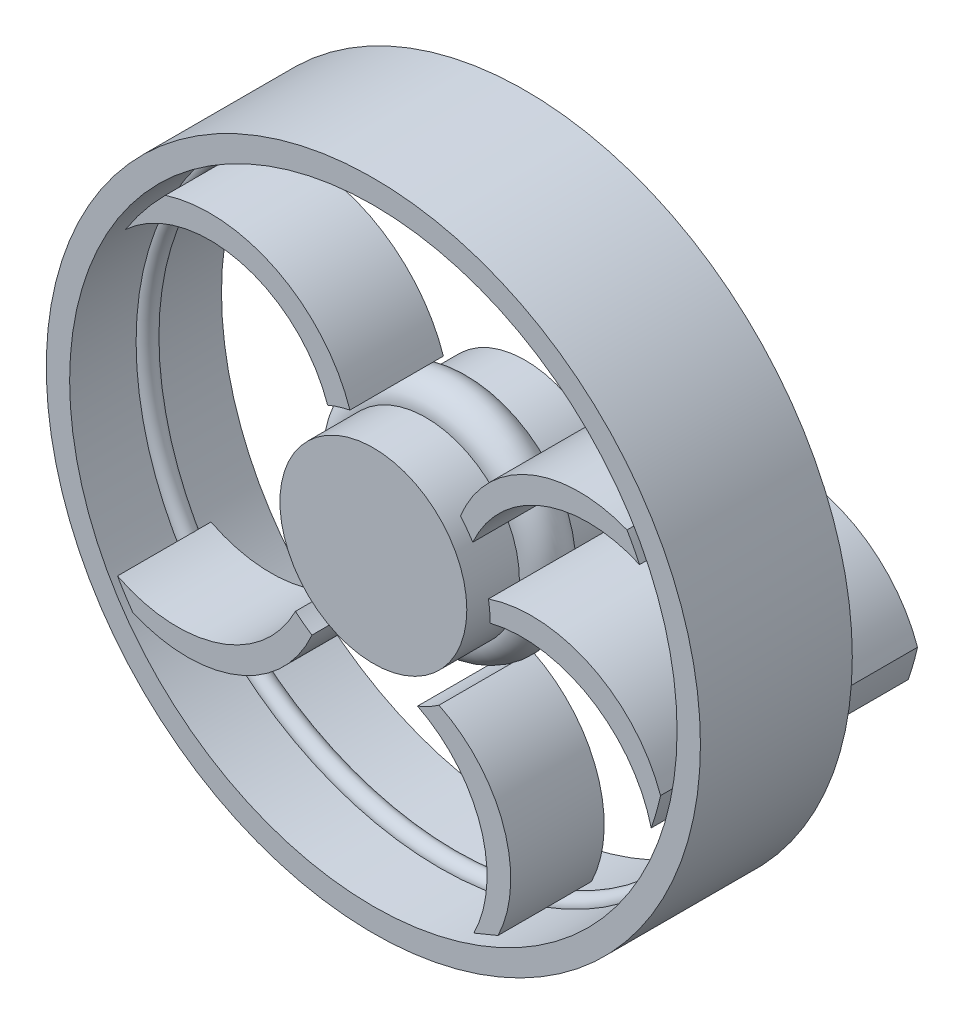
SolidWorks part; units mm, degrees
ref_plane "Front Plane" through (0, 0, 0) normal (0, 0, 1) x (1, 0, 0)
ref_plane "Top Plane" through (0, 0, 0) normal (0, 1, 0) x (1, 0, 0)
ref_plane "Right Plane" through (0, 0, 0) normal (1, 0, 0) x (0, 0, -1)
sketch "Sketch1" plane through (0, 0, 0) normal (0, 1, 0) x (1, 0, 0)
  line L0 (0, 0) -> (0, 65)
  line L1 (40, 65) -> (40, 42.5)
  line L2 (0, 65) -> (40, 65)
  line L3 (40, 22.5) -> (40, 0)
  line L4 (0, 0) -> (40, 0)
  line L5 (130, 36.5517) -> (130, 65)
  line L6 (140, 65) -> (140, 0)
  line L8 (140, 0) -> (130, 0)
  line L9 (130, 0) -> (130, 28.4483)
  line L10 (130, 65) -> (140, 65)
  arc A0 (40, 22.5) -> (40, 42.5) centre (40, 32.5) ccw
  arc A1 (130, 36.5517) -> (130, 28.4483) centre (130, 32.5) ccw
  dimension "D4" = 10
  dimension "D1" = 65
  dimension "D2" = 40
  dimension "D3" = 100
  dimension "D5" = 10
revolve "Revolve3" add sketch "Sketch1" angle 360 about L0
sketch "Sketch2" plane through (0, 0, 0) normal (0, 0, 1) x (1, 0, 0)
  arc A0 (-89.0385, 89.0792) -> (-10.0164, 48.9865) centre (-69.9577, 28.7652) cw
  circle A1 centre (0, 0) radius 125.9483 construction
  circle A2 centre (0, 0) radius 50 construction
  arc A3 (-106.0693, 67.9137) -> (-19.5672, 46.0122) centre (-69.9577, 28.7652) cw
  arc A4 (-86.0223, 79.5449) -> (-19.4917, 45.7899) centre (-69.9577, 28.7652) cw construction
  arc A5 (-89.0792, -89.0385) -> (-67.9137, -106.0693) centre (0, 0) ccw
  arc A6 (67.9137, 106.0693) -> (46.0122, 19.5672) centre (28.7652, 69.9577) cw
  arc A7 (89.0792, 89.0385) -> (48.9865, 10.0164) centre (28.7652, 69.9577) cw
  arc A8 (106.0693, -67.9137) -> (19.5672, -46.0122) centre (69.9577, -28.7652) cw
  arc A9 (89.0385, -89.0792) -> (10.0164, -48.9865) centre (69.9577, -28.7652) cw
  arc A10 (-67.9137, -106.0693) -> (-46.0122, -19.5672) centre (-28.7652, -69.9577) cw
  arc A11 (-89.0792, -89.0385) -> (-48.9865, -10.0164) centre (-28.7652, -69.9577) cw
  arc A12 (89.0385, -89.0792) -> (106.0693, -67.9137) centre (0, 0) ccw
  arc A13 (89.0792, 89.0385) -> (67.9137, 106.0693) centre (0, 0) ccw
  arc A14 (-89.0385, 89.0792) -> (-106.0693, 67.9137) centre (0, 0) ccw
  arc A15 (-48.9865, -10.0164) -> (-46.0122, -19.5672) centre (0, 0) ccw
  arc A16 (-10.0164, 48.9865) -> (-19.5672, 46.0122) centre (0, 0) ccw
  arc A17 (48.9865, 10.0164) -> (46.0122, 19.5672) centre (0, 0) ccw
  arc A18 (10.0164, -48.9865) -> (19.5672, -46.0122) centre (0, 0) ccw
  circle A19 centre (0, 0) radius 40 construction
  point P36 (0, 0)
  dimension "D3" = 63.2603
  dimension "D4" = 10.0164
  dimension "D5" = 19.5672
  dimension "D1" = 10
  dimension "D2" = 4
extrude "Boss-Extrude2" add sketch "Sketch2" against normal blind 40 separate body contours A3 A16 A0 A14
sketch "Sketch5" plane through (0, 0, 0) normal (0, 0, 1) x (1, 0, 0)
  arc A0 (50, 0) -> (118.932, -41.4505) centre (63.7407, -55.1912) cw
  circle A1 centre (0, 0) radius 50 construction
  circle A2 centre (0, 0) radius 125.9483 construction
  arc A3 (49.2509, 8.6226) -> (122.9195, -27.4549) centre (67.7415, -46.8732) cw
  circle A4 centre (0, 0) radius 40 construction
  arc A5 (118.932, -41.4505) -> (122.9195, -27.4549) centre (0, 0) ccw
  arc A6 (50, 0) -> (49.2509, 8.6226) centre (0, 0) ccw
  dimension "D1" = 56.876
  dimension "D2" = 58.4952
  dimension "D3" = 49.2509
  dimension "D4" = 50
  dimension "D5" = 63.7407
  dimension "D6" = 67.7415
extrude "Boss-Extrude3" add sketch "Sketch5" against normal blind 110 separate body contours A0 A5 A3 A6
sketch "Sketch6" plane through (0, 0, 0) normal (0, 0, 1) x (1, 0, 0)
  arc A0 (-33.3349, -37.2664) -> (-109.4975, -62.2355) centre (-83.9007, -11.6696) cw
  circle A1 centre (0, 0) radius 50 construction
  circle A2 centre (0, 0) radius 125.9483 construction
  arc A3 (-26.2706, -42.5424) -> (-103.0222, -72.4527) centre (-79.6016, -19.1218) cw
  arc A4 (-109.4975, -62.2355) -> (-103.0222, -72.4527) centre (0, 0) ccw
  arc A5 (-33.3349, -37.2664) -> (-26.2706, -42.5424) centre (0, 0) ccw
  circle A6 centre (0, 0) radius 40 construction
  dimension "D1" = 56.6754
  dimension "D2" = 58.247
  dimension "D3" = 26.2706
  dimension "D4" = 33.3349
  dimension "D5" = 79.6016
  dimension "D6" = 83.9007
extrude "Boss-Extrude4" add sketch "Sketch6" against normal blind 40 separate body contours A3 A4 A0 A5
sketch "Sketch7" plane through (0, 0, 0) normal (0, 0, 1) x (1, 0, 0)
  circle A0 centre (0, 0) radius 50 construction
  arc A2 (37.2664, 33.3349) -> (108.5692, 63.8411) centre (88.1709, 12.9366) cw
  circle A3 centre (0, 0) radius 125.9483 construction
  arc A4 (42.5424, 26.2706) -> (113.9403, 53.671) centre (91.9415, 4.2719) cw
  arc A5 (42.5424, 26.2706) -> (37.2664, 33.3349) centre (0, 0) ccw
  arc A6 (113.9403, 53.671) -> (108.5692, 63.8411) centre (0, 0) ccw
  dimension "D1" = 54.8394
  dimension "D2" = 54.0761
  dimension "D3" = 38.9201
  dimension "D4" = 42.6906
  dimension "D5" = 59.3183
  dimension "D6" = 64.6894
extrude "Boss-Extrude5" add sketch "Sketch7" against normal blind 40 separate body contours A2 A6 A4 A5
sketch "Sketch8" plane through (0, 0, 0) normal (0, 0, 1) x (1, 0, 0)
  line L0 (43.0126, -118.376) -> (53.3713, -114.0776)
  circle A0 centre (0, 0) radius 50 construction
  arc A2 (28.0803, -41.3702) -> (53.3713, -114.0776) centre (4.3721, -90.3694) cw
  arc A3 (18.9063, -46.2877) -> (43.0126, -118.376) centre (-5.1111, -94.3938) cw
  circle A4 centre (0, 0) radius 125.9483 construction
  arc A5 (18.9063, -46.2877) -> (28.0803, -41.3702) centre (0, 0) ccw
  circle A7 centre (0, 0) radius 40 construction
  dimension "D1" = 54.4335
  dimension "D2" = 53.7683
  dimension "D3" = 4.3721
  dimension "D4" = 18.9063
  dimension "D5" = 28.0803
  dimension "D6" = 43.0126
  dimension "D7" = 53.3713
extrude "Boss-Extrude6" add sketch "Sketch8" against normal blind 40 separate body contours A3 L0 A2 A5
